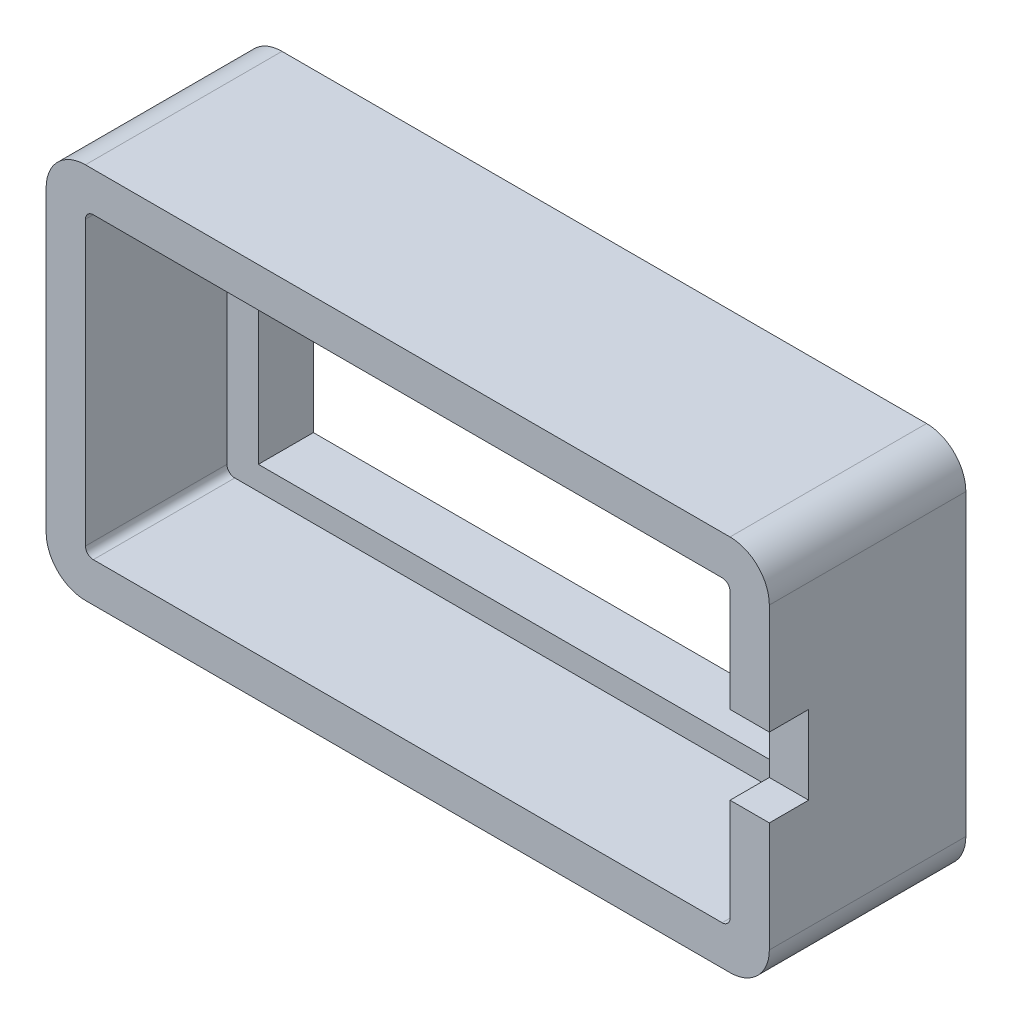
SolidWorks part; units mm, degrees
ref_plane "Alzado" through (0, 0, 0) normal (0, 0, 1) x (1, 0, 0)
ref_plane "Planta" through (0, 0, 0) normal (0, 1, 0) x (1, 0, 0)
ref_plane "Vista lateral" through (0, 0, 0) normal (1, 0, 0) x (0, 0, -1)
sketch "Croquis7" plane through (0, 0, 0) normal (0, 0, 1) x (1, 0, 0)
  line L1 (0, 0) -> (74, 0)
  line L2 (0, 0) -> (0, -29)
  line L3 (0, -29) -> (74, -29)
  line L4 (74, 0) -> (74, -29)
  line L5 (-9, -37) -> (83, -37)
  line L6 (-9, -37) -> (-9, 11)
  line L7 (-9, 11) -> (83, 11)
  line L8 (83, -37) -> (83, 11)
  dimension "D1" = 29
  dimension "D2" = 74
  dimension "D3" = 9
  dimension "D4" = 9
  dimension "D5" = 11
  dimension "D6" = 8
extrude "Saliente-Extruir5" add sketch "Croquis7" along normal blind 25
sketch "Croquis8" plane through (0, 0, 25) normal (0, 0, 1) x (1, 0, 0)
  line L0 (-9, 11) -> (-9, -37) construction
  line L1 (-4, 6) -> (78, 6)
  line L2 (-4, 6) -> (-4, -32)
  line L3 (-4, -32) -> (78, -32)
  line L4 (78, 6) -> (78, -32)
  line L5 (83, 11) -> (-9, 11) construction
  line L6 (83, -37) -> (83, 11) construction
  line L7 (-9, -37) -> (83, -37) construction
  dimension "D1" = 5
  dimension "D2" = 5
  dimension "D3" = 5
  dimension "D4" = 5
extrude "Cortar-Extruir3" cut sketch "Croquis8" against normal blind 18
fillet "Redondeo1" radius 5 4 edges at (-9, -37, 12.5) (-9, 11, 12.5) (83, 11, 12.5) (83, -37, 12.5)
fillet "Redondeo2" radius 1 4 edges at (-4, 6, 16) (-4, -32, 16) (78, 6, 16) (78, -32, 16)
sketch "Croquis10" plane through (83, 0, 0) normal (1, 0, 0) x (0, 0, -1)
  line L0 (-25, -32) -> (-25, 6) construction
  line L1 (-30, -8) -> (-20, -8)
  line L2 (-30, -8) -> (-30, -18)
  line L3 (-30, -18) -> (-20, -18)
  line L4 (-20, -8) -> (-20, -18)
  line L5 (-30, -8) -> (-20, -18) construction
  line L6 (-30, -18) -> (-20, -8) construction
  point P0 (-25, -13)
  dimension "D1" = 10
  dimension "D2" = 10
extrude "Cortar-Extruir4" cut sketch "Croquis10" against normal blind 20
